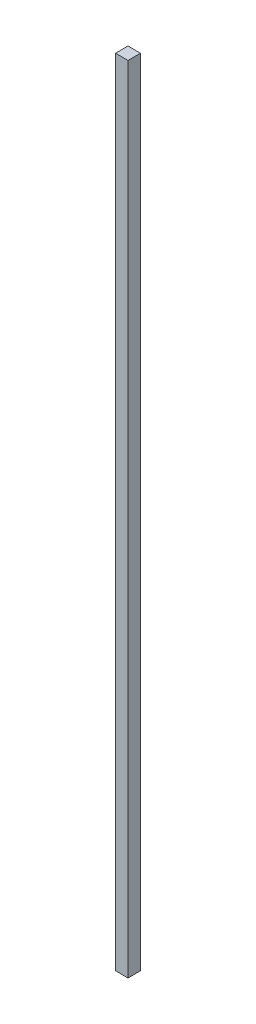
SolidWorks part; units mm, degrees
ref_plane "Спереди" through (0, 0, 0) normal (0, 0, 1) x (1, 0, 0)
ref_plane "Сверху" through (0, 0, 0) normal (0, 1, 0) x (1, 0, 0)
ref_plane "Справа" through (0, 0, 0) normal (1, 0, 0) x (0, 0, -1)
sketch "Эскиз1" plane through (0, 0, 0) normal (0, 1, 0) x (1, 0, 0)
  line L1 (-42.5311, 16.6754) -> (7.4689, 16.6754)
  line L2 (-42.5311, 16.6754) -> (-42.5311, -33.3246)
  line L3 (-42.5311, -33.3246) -> (7.4689, -33.3246)
  line L4 (7.4689, 16.6754) -> (7.4689, -33.3246)
extrude "Бобышка-Вытянуть1" add sketch "Эскиз1" along normal blind 3180
